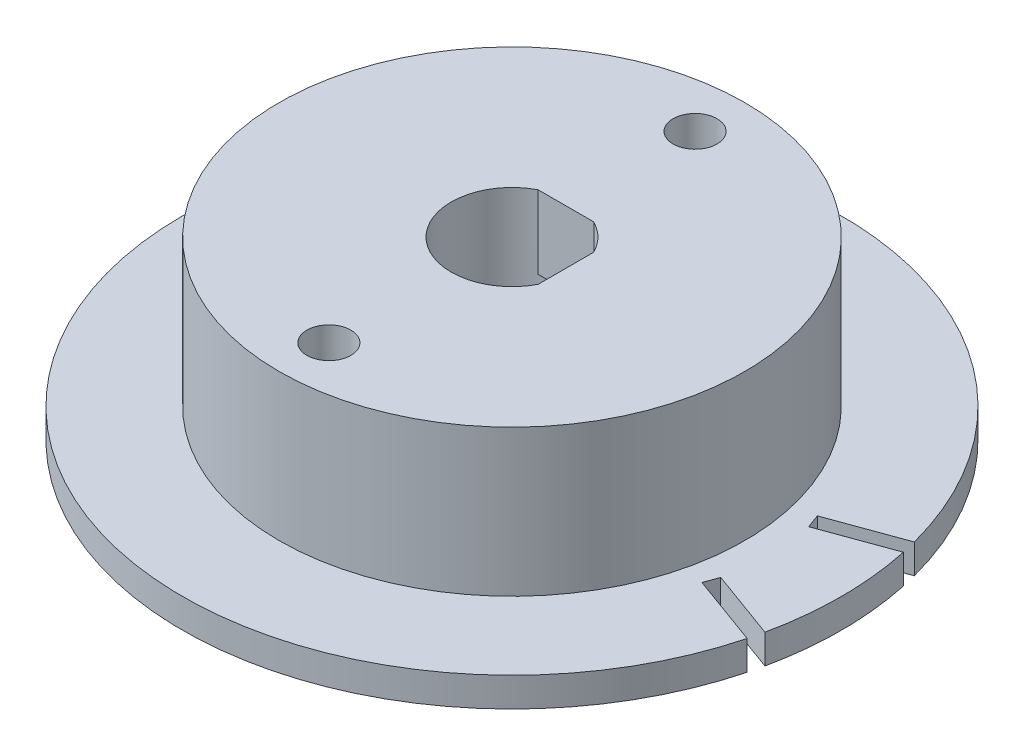
SolidWorks part; units mm, degrees
ref_plane "Спереди" through (0, 0, 0) normal (0, 0, 1) x (1, 0, 0)
ref_plane "Сверху" through (0, 0, 0) normal (0, 1, 0) x (1, 0, 0)
ref_plane "Справа" through (0, 0, 0) normal (1, 0, 0) x (0, 0, -1)
sketch "Эскиз1" plane through (0, 0, 0) normal (0, 1, 0) x (1, 0, 0)
  circle A0 centre (0, 0) radius 15.9
  dimension "D1" = 31.8
extrude "Вытянуть1" add sketch "Эскиз1" along normal blind 10
sketch "Эскиз2" plane through (0, 0, 0) normal (0, -1, 0) x (1, 0, 0)
  circle A0 centre (0, 0) radius 22.5
  dimension "D1" = 45
extrude "Вытянуть2" add sketch "Эскиз2" along normal blind 2
sketch "Эскиз3" plane through (0, 10, 0) normal (0, 1, 0) x (1, 0, 0)
  circle A0 centre (0, 12.5) radius 1.5
  circle A1 centre (0, -12.5) radius 1.5
  circle A2 centre (0, 0) radius 12.5 construction
  dimension "D1" = 25
  dimension "D2" = 3
extrude "Вытянуть3" cut sketch "Эскиз3" against normal blind 3
sketch "Эскиз4" plane through (0, 0, 0) normal (0, 1, 0) x (1, 0, 0)
  line L0 (21.7645, 5.7058) -> (16.9122, 3.9397)
  line L1 (16.9122, 3.9397) -> (17.2542, 3)
  line L2 (17.2542, 3) -> (21.9979, 4.7266)
  line L3 (0, 0) -> (22.5, 0) construction
  line L4 (17.2542, -3) -> (21.9979, -4.7266)
  line L5 (16.9122, -3.9397) -> (17.2542, -3)
  line L6 (21.7645, -5.7058) -> (16.9122, -3.9397)
  arc A0 (21.7645, 5.7058) -> (21.9979, 4.7266) centre (0, 0) cw
  circle A1 centre (0, 0) radius 22.5 construction
  arc A2 (21.9979, -4.7266) -> (21.7645, -5.7058) centre (0, 0) cw
  dimension "D1" = 1
  dimension "D2" = 20
  dimension "D3" = 3
extrude "Вытянуть4" cut sketch "Эскиз4" against normal blind 3
sketch "Эскиз5" plane through (0, 10, 0) normal (0, 1, 0) x (1, 0, 0)
  line L0 (3.6895, 1.9) -> (3.6895, -1.9)
  line L1 (1.9, 3.6895) -> (-1.9, 3.6895)
  circle A0 centre (0, 0) radius 4.15 construction
  arc A1 (1.9, 3.6895) -> (3.6895, 1.9) centre (0, 0) cw
  arc A2 (-1.9, 3.6895) -> (3.6895, -1.9) centre (0, 0) ccw
  dimension "D1" = 8.3
  dimension "D2" = 3.8
extrude "Вытянуть5" cut sketch "Эскиз5" against normal blind 5
sketch "Эскиз6" plane through (0, -2, 0) normal (0, -1, 0) x (1, 0, 0)
  circle A0 centre (0, 0) radius 4.15
  dimension "D1" = 8.3
extrude "Вытянуть6" cut sketch "Эскиз6" against normal up to surface (7 mm away) up to face at (0.9224, 5, -0.9224)
chamfer "Фаска1" distance 1 angle 45 1 edges at (0, -2, -4.15)
